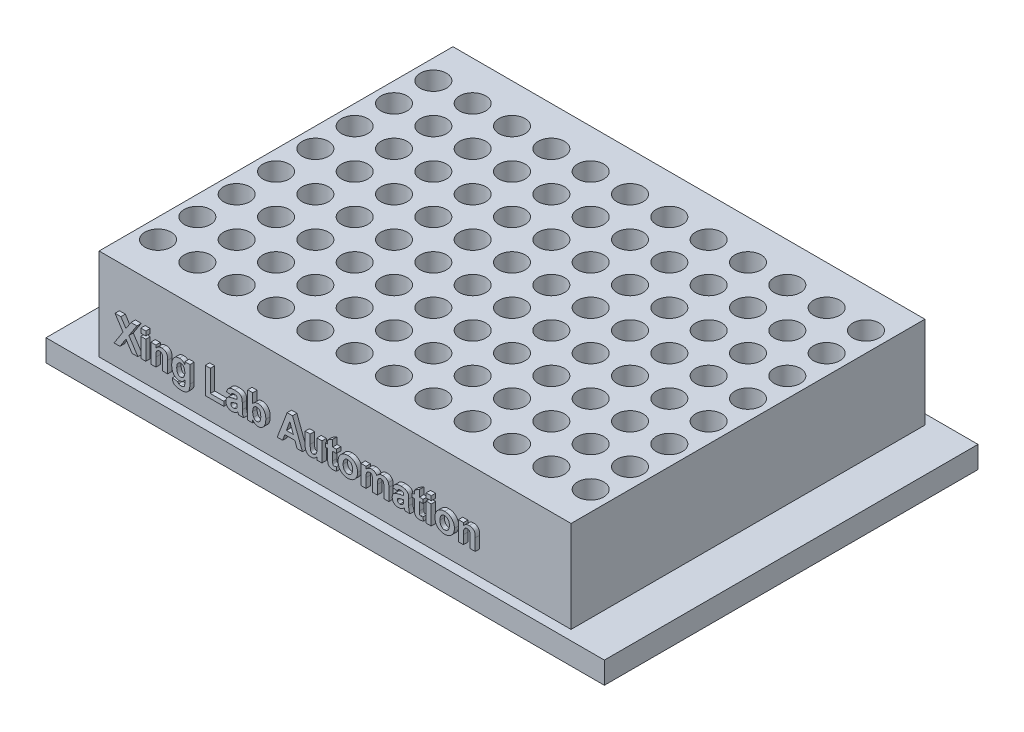
SolidWorks part; units mm, degrees
ref_plane "前视基准面" through (0, 0, 0) normal (0, 0, 1) x (1, 0, 0)
ref_plane "上视基准面" through (0, 0, 0) normal (0, 1, 0) x (1, 0, 0)
ref_plane "右视基准面" through (0, 0, 0) normal (1, 0, 0) x (0, 0, -1)
other "Configuration Table"
sketch "草图1" plane through (0, 0, 0) normal (0, 1, 0) x (1, 0, 0)
  line L1 (-63.885, 42.75) -> (63.885, 42.75)
  line L2 (-63.885, 42.75) -> (-63.885, -42.75)
  line L3 (-63.885, -42.75) -> (63.885, -42.75)
  line L4 (63.885, 42.75) -> (63.885, -42.75)
  line L5 (-63.885, 42.75) -> (63.885, -42.75) construction
  line L6 (-63.885, -42.75) -> (63.885, 42.75) construction
  point P0 (0, 0)
  dimension "D1" = 127.77
  dimension "D2" = 85.5
extrude "凸台-拉伸1" add sketch "草图1" along normal blind 5
sketch "草图2" plane through (0, 5, 0) normal (0, 1, 0) x (1, 0, 0)
  line L0 (49.5, 31.5) -> (40.5, 31.5) construction
  line L1 (-54, 40.485) -> (54, 40.485)
  line L2 (-54, 40.485) -> (-54, -40.485)
  line L3 (-54, -40.485) -> (54, -40.485)
  line L4 (54, 40.485) -> (54, -40.485)
  line L5 (-54, 40.485) -> (54, -40.485) construction
  line L6 (-54, -40.485) -> (54, 40.485) construction
  circle A0 centre (49.5, 31.5) radius 3
  circle A1 centre (40.5, 31.5) radius 3
  circle A2 centre (31.5, 31.5) radius 3
  circle A3 centre (22.5, 31.5) radius 3
  circle A4 centre (13.5, 31.5) radius 3
  circle A5 centre (4.5, 31.5) radius 3
  circle A6 centre (-4.5, 31.5) radius 3
  circle A7 centre (-13.5, 31.5) radius 3
  circle A8 centre (-22.5, 31.5) radius 3
  circle A9 centre (-31.5, 31.5) radius 3
  circle A10 centre (-40.5, 31.5) radius 3
  circle A11 centre (-49.5, 31.5) radius 3
  circle A12 centre (40.5, 22.5) radius 3
  circle A13 centre (31.5, 22.5) radius 3
  circle A14 centre (22.5, 22.5) radius 3
  circle A15 centre (13.5, 22.5) radius 3
  circle A16 centre (4.5, 22.5) radius 3
  circle A17 centre (-4.5, 22.5) radius 3
  circle A18 centre (-13.5, 22.5) radius 3
  circle A19 centre (-22.5, 22.5) radius 3
  circle A20 centre (-31.5, 22.5) radius 3
  circle A21 centre (-40.5, 22.5) radius 3
  circle A22 centre (-49.5, 22.5) radius 3
  circle A23 centre (40.5, 13.5) radius 3
  circle A24 centre (31.5, 13.5) radius 3
  circle A25 centre (22.5, 13.5) radius 3
  circle A26 centre (13.5, 13.5) radius 3
  circle A27 centre (4.5, 13.5) radius 3
  circle A28 centre (-4.5, 13.5) radius 3
  circle A29 centre (-13.5, 13.5) radius 3
  circle A30 centre (-22.5, 13.5) radius 3
  circle A31 centre (-31.5, 13.5) radius 3
  circle A32 centre (-40.5, 13.5) radius 3
  circle A33 centre (-49.5, 13.5) radius 3
  circle A34 centre (40.5, 4.5) radius 3
  circle A35 centre (31.5, 4.5) radius 3
  circle A36 centre (22.5, 4.5) radius 3
  circle A37 centre (13.5, 4.5) radius 3
  circle A38 centre (4.5, 4.5) radius 3
  circle A39 centre (-4.5, 4.5) radius 3
  circle A40 centre (-13.5, 4.5) radius 3
  circle A41 centre (-22.5, 4.5) radius 3
  circle A42 centre (-31.5, 4.5) radius 3
  circle A43 centre (-40.5, 4.5) radius 3
  circle A44 centre (-49.5, 4.5) radius 3
  circle A45 centre (40.5, -4.5) radius 3
  circle A46 centre (31.5, -4.5) radius 3
  circle A47 centre (22.5, -4.5) radius 3
  circle A48 centre (13.5, -4.5) radius 3
  circle A49 centre (4.5, -4.5) radius 3
  circle A50 centre (-4.5, -4.5) radius 3
  circle A51 centre (-13.5, -4.5) radius 3
  circle A52 centre (-22.5, -4.5) radius 3
  circle A53 centre (-31.5, -4.5) radius 3
  circle A54 centre (-40.5, -4.5) radius 3
  circle A55 centre (-49.5, -4.5) radius 3
  circle A56 centre (40.5, -13.5) radius 3
  circle A57 centre (31.5, -13.5) radius 3
  circle A58 centre (22.5, -13.5) radius 3
  circle A59 centre (13.5, -13.5) radius 3
  circle A60 centre (4.5, -13.5) radius 3
  circle A61 centre (-4.5, -13.5) radius 3
  circle A62 centre (-13.5, -13.5) radius 3
  circle A63 centre (-22.5, -13.5) radius 3
  circle A64 centre (-31.5, -13.5) radius 3
  circle A65 centre (-40.5, -13.5) radius 3
  circle A66 centre (-49.5, -13.5) radius 3
  circle A67 centre (40.5, -22.5) radius 3
  circle A68 centre (31.5, -22.5) radius 3
  circle A69 centre (22.5, -22.5) radius 3
  circle A70 centre (13.5, -22.5) radius 3
  circle A71 centre (4.5, -22.5) radius 3
  circle A72 centre (-4.5, -22.5) radius 3
  circle A73 centre (-13.5, -22.5) radius 3
  circle A74 centre (-22.5, -22.5) radius 3
  circle A75 centre (-31.5, -22.5) radius 3
  circle A76 centre (-40.5, -22.5) radius 3
  circle A77 centre (-49.5, -22.5) radius 3
  circle A78 centre (40.5, -31.5) radius 3
  circle A79 centre (31.5, -31.5) radius 3
  circle A80 centre (22.5, -31.5) radius 3
  circle A81 centre (13.5, -31.5) radius 3
  circle A82 centre (4.5, -31.5) radius 3
  circle A83 centre (-4.5, -31.5) radius 3
  circle A84 centre (-13.5, -31.5) radius 3
  circle A85 centre (-22.5, -31.5) radius 3
  circle A86 centre (-31.5, -31.5) radius 3
  circle A87 centre (-40.5, -31.5) radius 3
  circle A88 centre (-49.5, -31.5) radius 3
  circle A89 centre (49.5, 22.5) radius 3
  circle A90 centre (49.5, 13.5) radius 3
  circle A91 centre (49.5, 4.5) radius 3
  circle A92 centre (49.5, -4.5) radius 3
  circle A93 centre (49.5, -13.5) radius 3
  circle A94 centre (49.5, -22.5) radius 3
  circle A95 centre (49.5, -31.5) radius 3
  point P0 (0, 0)
  dimension "D2" = 12
  dimension "D1" = 80.97
  dimension "121.26" = 108
  dimension "D4" = 9
  dimension "D3" = 8
extrude "凸台-拉伸6" add sketch "草图2" along normal blind 21
sketch "草图4" plane through (0, 0, 40.485) normal (0, 0, 1) x (1, 0, 0)
  text T0 "<b>Xing Lab Automation</b>" font "Helvetica" height 6
extrude "凸台-拉伸8" add sketch "草图4" along normal blind 1
